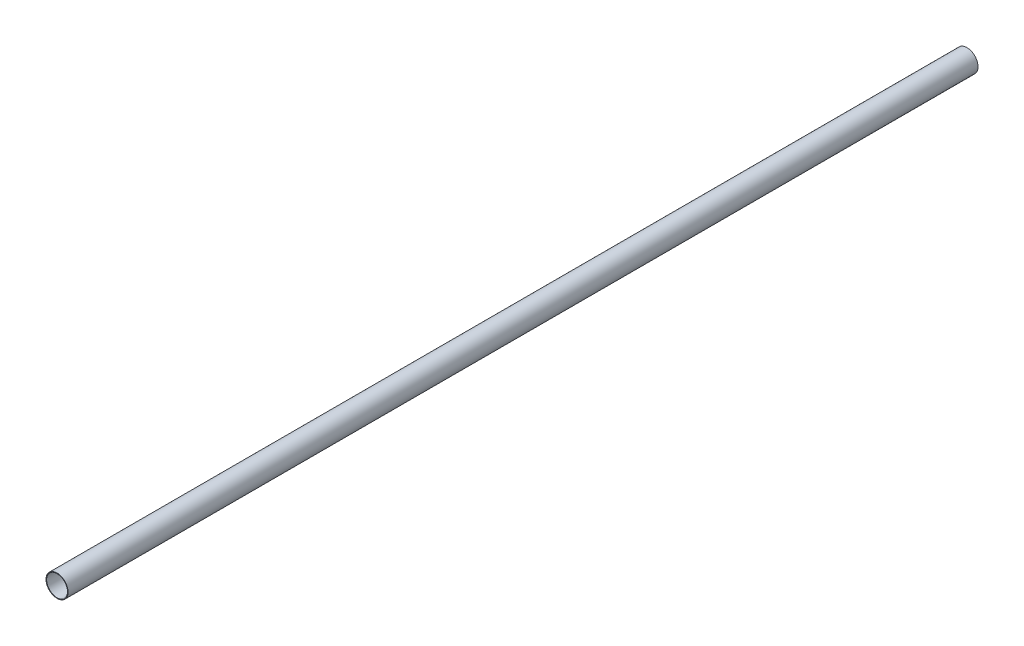
SolidWorks part; units mm, degrees
ref_plane "Front Plane" through (0, 0, 0) normal (0, 0, 1) x (1, 0, 0)
ref_plane "Top Plane" through (0, 0, 0) normal (0, 1, 0) x (1, 0, 0)
ref_plane "Right Plane" through (0, 0, 0) normal (1, 0, 0) x (0, 0, -1)
sketch "Sketch1" plane through (0, 0, 0) normal (0, 0, 1) x (1, 0, 0)
  circle A0 centre (0, 0) radius 11.25
  circle A1 centre (0, 0) radius 10.65
  dimension "D1" = 22.5
  dimension "D2" = 0.6
extrude "Boss-Extrude1" add sketch "Sketch1" along normal blind 927.5
